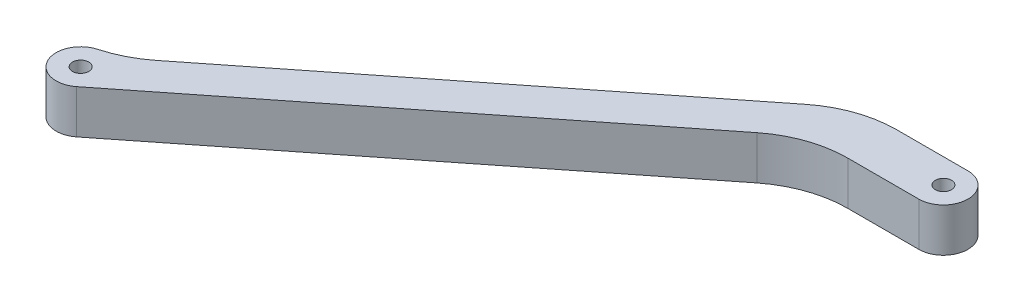
SolidWorks part; units mm, degrees
ref_plane "Front Plane" through (0, 0, 0) normal (0, 0, 1) x (1, 0, 0)
ref_plane "Top Plane" through (0, 0, 0) normal (0, 1, 0) x (1, 0, 0)
ref_plane "Right Plane" through (0, 0, 0) normal (1, 0, 0) x (0, 0, -1)
sketch "Sketch1" plane through (0, 0, 0) normal (0, 1, 0) x (1, 0, 0)
  line L0 (39, 27.95) -> (1.395, -1.7654)
  line L1 (39, 27.95) -> (49, 27.95)
  line L2 (39, 27.95) -> (39, 32.45)
  line L3 (39, 32.45) -> (49, 32.45)
  line L4 (49, 27.95) -> (49, 32.45)
  line L5 (0.6574, 2.1518) -> (39, 32.45)
  circle A0 centre (48.5037, 15.2082) radius 2 construction
  circle A3 centre (48.5037, 15.2082) radius 2 construction
  circle A4 centre (49, 30.2) radius 0.75
  circle A6 centre (49, 30.2) radius 2.25
  circle A7 centre (0, 0) radius 0.75
  circle A8 centre (0, 0) radius 2.25
  dimension "D5" = 1.5
  dimension "D1" = 1.5
  dimension "D2" = 10
  dimension "D3" = 49
  dimension "D4" = 30.2
extrude "Boss-Extrude1" add sketch "Sketch1" against normal blind 4
fillet "Fillet1" radius 10 3 edges at (39, -2, -27.95) (0.6574, -2, -2.1518) (39, -2, -32.45)
equation "\"D3@Sketch1\"= \"pivot distance@R4E-MLCar-0100 Steering Assembly.Assembly\""
